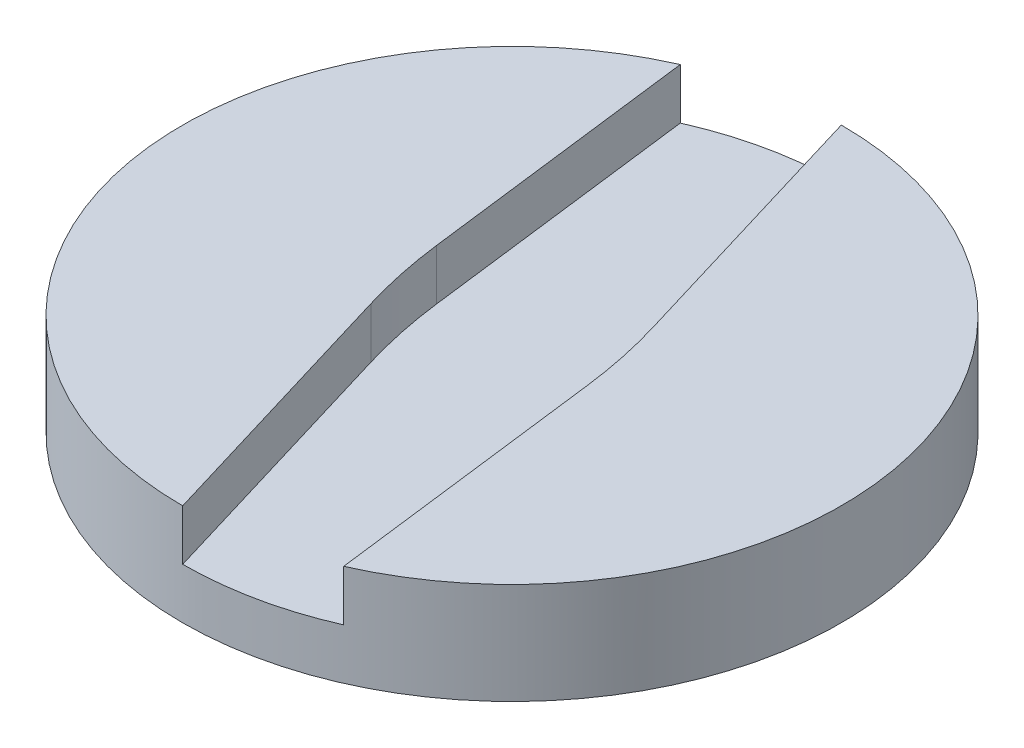
SolidWorks part; units mm, degrees
ref_plane "Alzado" through (0, 0, 0) normal (0, 0, 1) x (1, 0, 0)
ref_plane "Planta" through (0, 0, 0) normal (0, 1, 0) x (1, 0, 0)
ref_plane "Vista lateral" through (0, 0, 0) normal (1, 0, 0) x (0, 0, -1)
sketch "Croquis1" plane through (0, 0, 0) normal (0, 1, 0) x (1, 0, 0)
  circle A0 centre (0, 0) radius 13
  dimension "D1" = 26
extrude "Saliente-Extruir1" add sketch "Croquis1" along normal blind 4
sketch "Croquis3" plane through (0, 4, 0) normal (0, 1, 0) x (1, 0, 0)
  circle A0 centre (0, 0) radius 3.6385 construction
sketch "Croquis4" plane through (0, 4, 0) normal (0, 1, 0) x (1, 0, 0)
  line L4 (-3.184, -2.3872) -> (0.6567, -15.1514)
  line L5 (5.5313, -14.1209) -> (3.8777, -0.8943)
  line L6 (3.184, 2.3872) -> (-0.6567, 15.1514)
  line L7 (-5.5313, 14.1209) -> (-3.8777, 0.8943)
  arc A6 (0.6567, -15.1514) -> (5.5313, -14.1209) centre (3.0506, -14.4311) ccw
  arc A7 (-0.6567, 15.1514) -> (-5.5313, 14.1209) centre (-3.0506, 14.4311) ccw
  arc A8 (-3.5998, -0.761) -> (-3.184, -2.3872) centre (15.9678, 3.3755) ccw
  arc A9 (-3.8777, 0.8943) -> (-3.5998, -0.761) centre (15.9678, 3.3755) ccw
  arc A10 (3.5998, 0.761) -> (3.184, 2.3872) centre (-15.9678, -3.3755) ccw
  arc A11 (3.8777, -0.8943) -> (3.5998, 0.761) centre (-15.9678, -3.3755) ccw
extrude "Cortar-Extruir1" cut sketch "Croquis4" against normal blind 2
